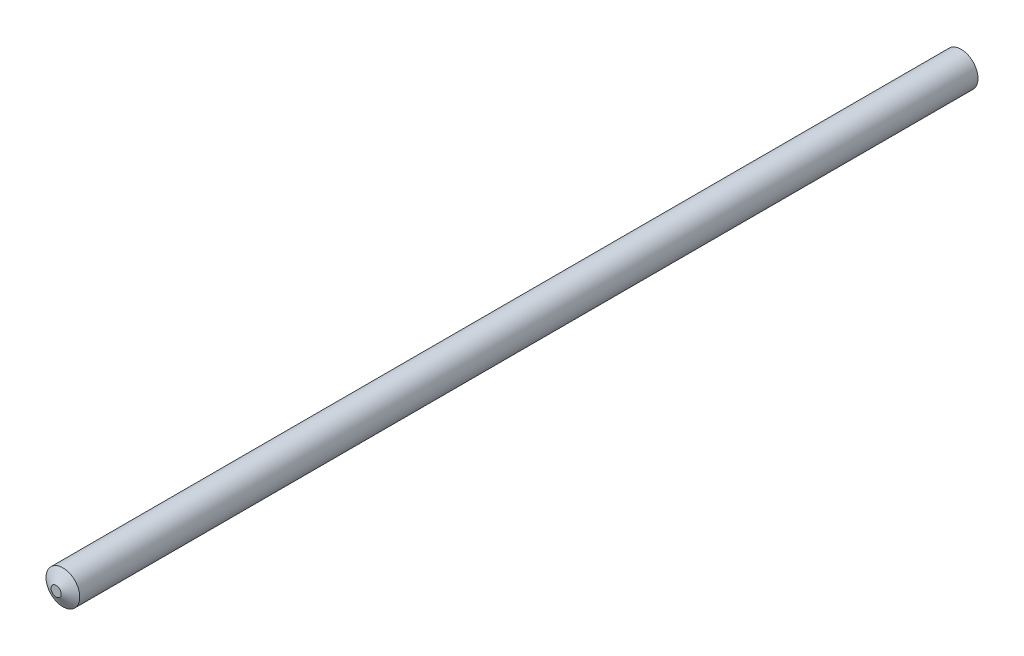
SolidWorks part; units mm, degrees
ref_plane "Alzado" through (0, 0, 0) normal (0, 0, 1) x (1, 0, 0)
ref_plane "Planta" through (0, 0, 0) normal (0, 1, 0) x (1, 0, 0)
ref_plane "Vista lateral" through (0, 0, 0) normal (1, 0, 0) x (0, 0, -1)
sketch "Croquis1" plane through (0, 0, 0) normal (0, 0, 1) x (1, 0, 0)
  circle A0 centre (0, 0) radius 5
extrude "Saliente-Extruir1" add sketch "Croquis1" along normal blind 270
sketch "Croquis3" plane through (0, 0, 0) normal (0, 1, 0) x (1, 0, 0)
  line L0 (1.5, -270) -> (5, -267.9996)
  line L1 (-5, -270) -> (5, -270) construction
  line L2 (5, -270) -> (5, 0) construction
  line L3 (5, -267.9996) -> (5, -270)
  line L4 (5, -270) -> (1.5, -270)
  dimension "D2" = 2.0004
sweep "Cortar-Barrer1" cut profiles "Croquis3" path edge at (5, 0, 270)
sketch "Croquis4" plane through (0, 0, 0) normal (0, 1, 0) x (1, 0, 0)
  line L0 (5, 0) -> (5, -2)
  line L1 (5, -267.9996) -> (5, 0) construction
  line L2 (5, 0) -> (1.5, 0)
  line L3 (5, 0) -> (-5, 0) construction
  line L4 (1.5, 0) -> (5, -2)
sweep "Cortar-Barrer2" cut profiles "Croquis4" path edge at (5, 0, 0)
